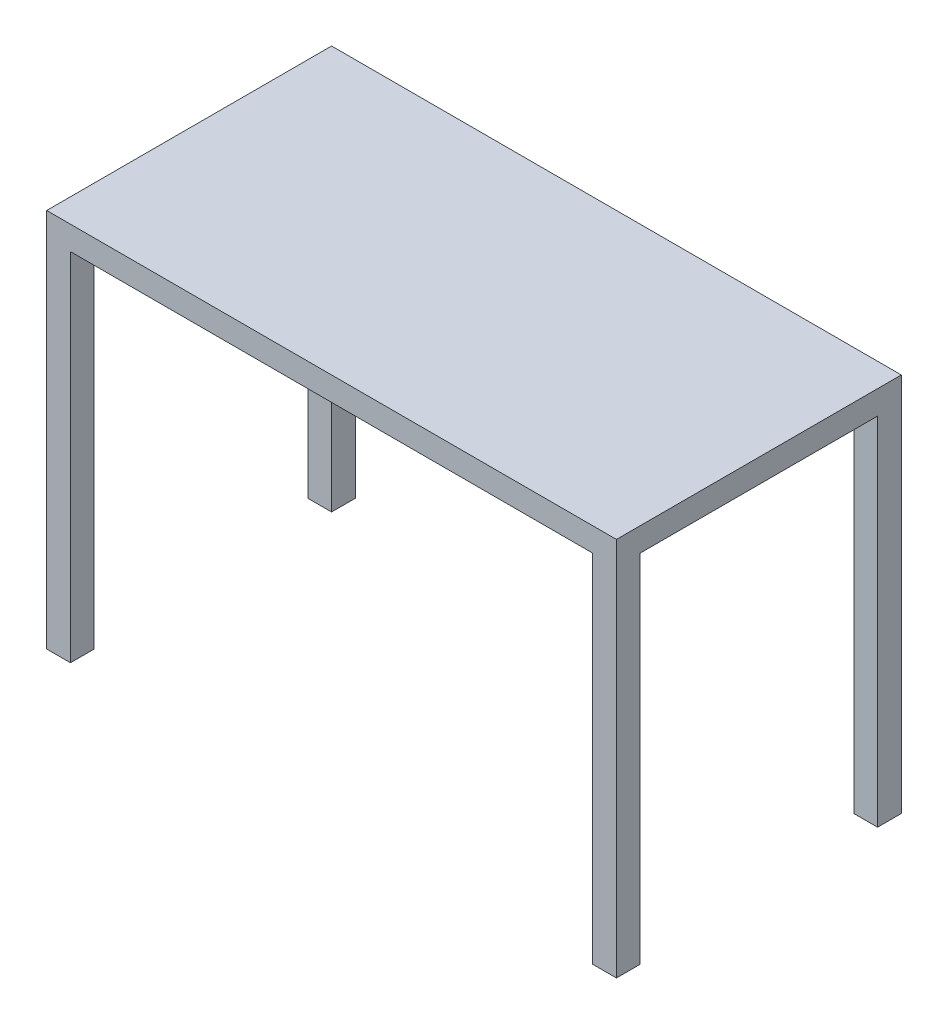
SolidWorks part; units mm, degrees
material "PVC Rigid"
ref_plane "Front" through (0, 0, 0) normal (0, 0, 1) x (1, 0, 0)
ref_plane "Top" through (0, 0, 0) normal (0, 1, 0) x (1, 0, 0)
ref_plane "Right" through (0, 0, 0) normal (1, 0, 0) x (0, 0, -1)
sketch "Sketch1" plane through (0, 0, 0) normal (0, 1, 0) x (1, 0, 0)
  line L1 (-914.4, 304.8) -> (914.4, 304.8)
  line L2 (-914.4, 304.8) -> (-914.4, -304.8)
  line L3 (-914.4, -304.8) -> (914.4, -304.8)
  line L4 (914.4, 304.8) -> (914.4, -304.8)
  line L5 (-914.4, 304.8) -> (914.4, -304.8) construction
  line L6 (-914.4, -304.8) -> (914.4, 304.8) construction
  point P0 (0, 0)
  dimension "D1" = 1828.8
  dimension "D2" = 609.6
extrude "Boss-Extrude1" add sketch "Sketch1" along normal blind 50.8
sketch "Sketch2" plane through (0, 0, 0) normal (0, -1, 0) x (1, 0, 0)
  line L1 (-914.4, 304.8) -> (-863.6, 304.8)
  line L2 (-914.4, 304.8) -> (-914.4, 254)
  line L3 (-914.4, 254) -> (-863.6, 254)
  line L4 (-863.6, 304.8) -> (-863.6, 254)
  line L5 (-914.4, -304.8) -> (-863.6, -304.8)
  line L6 (-914.4, -304.8) -> (-914.4, -254)
  line L7 (-914.4, -254) -> (-863.6, -254)
  line L8 (-863.6, -304.8) -> (-863.6, -254)
  line L9 (914.4, 304.8) -> (863.6, 304.8)
  line L10 (914.4, 304.8) -> (914.4, 254)
  line L11 (914.4, 254) -> (863.6, 254)
  line L12 (863.6, 304.8) -> (863.6, 254)
  line L13 (914.4, -304.8) -> (863.6, -304.8)
  line L14 (914.4, -304.8) -> (914.4, -254)
  line L15 (914.4, -254) -> (863.6, -254)
  line L16 (863.6, -304.8) -> (863.6, -254)
  dimension "D1" = 50.8
extrude "Boss-Extrude2" add sketch "Sketch2" along normal blind 762
sketch "Sketch3" plane through (0, 0, 304.8) normal (0, 0, 1) x (1, 0, 0)
  line L0 (-914.4, 50.8) -> (914.4, 50.8) construction
  line L1 (914.4, -762) -> (304.8, -762)
  line L2 (914.4, -762) -> (914.4, 50.8)
  line L3 (914.4, 50.8) -> (304.8, 50.8)
  line L4 (304.8, -762) -> (304.8, 50.8)
  dimension "D1" = 1219.2
extrude "Cut-Extrude1" cut sketch "Sketch3" against normal through all
sketch "Sketch4" plane through (0, 0, 0) normal (0, -1, 0) x (1, 0, 0)
  line L0 (-863.6, 304.8) -> (-914.4, 304.8) construction
  line L1 (304.8, 304.8) -> (254, 304.8)
  line L2 (304.8, 304.8) -> (304.8, 254)
  line L3 (304.8, 254) -> (254, 254)
  line L4 (254, 304.8) -> (254, 254)
  line L5 (304.8, -304.8) -> (254, -304.8)
  line L6 (304.8, -304.8) -> (304.8, -254)
  line L7 (304.8, -254) -> (254, -254)
  line L8 (254, -304.8) -> (254, -254)
extrude "Boss-Extrude3" add sketch "Sketch4" along normal up to surface (762 mm away) up to face at (-889, -762, 279.4)
